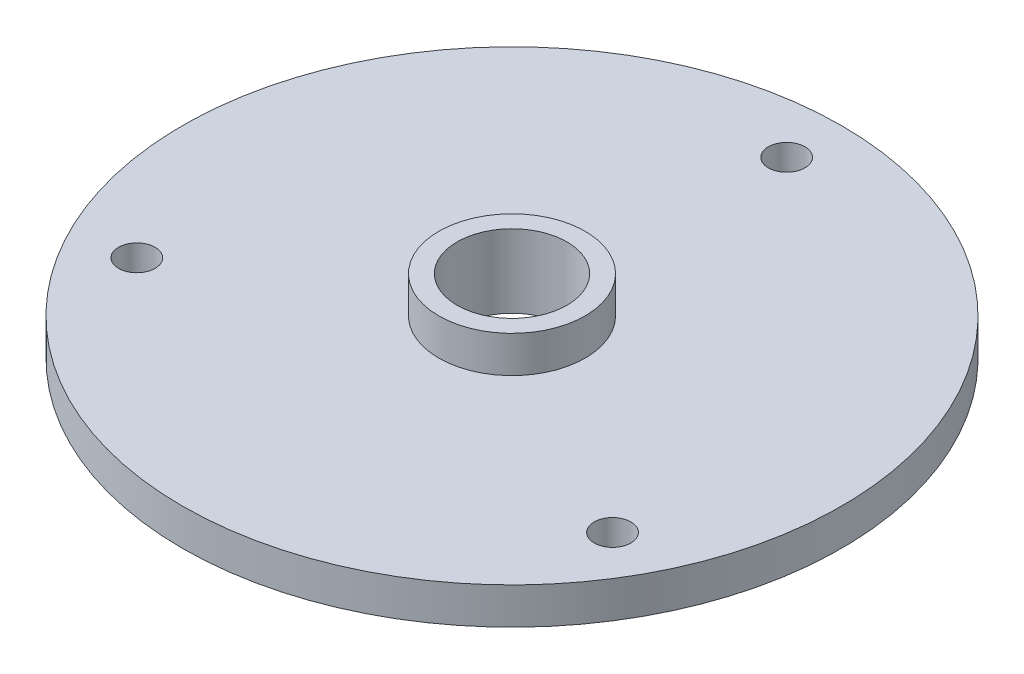
SolidWorks part; units mm, degrees
ref_plane "前视基准面" through (0, 0, 0) normal (0, 0, 1) x (1, 0, 0)
ref_plane "上视基准面" through (0, 0, 0) normal (0, 1, 0) x (1, 0, 0)
ref_plane "右视基准面" through (0, 0, 0) normal (1, 0, 0) x (0, 0, -1)
sketch "草图1" plane through (0, 0, 0) normal (0, 1, 0) x (1, 0, 0)
  line L0 (0, 0) -> (0, 22.2788) construction
  line L1 (0, 0) -> (39.8876, 0) construction
  circle A0 centre (0, 0) radius 18
  circle A1 centre (0, 0) radius 3
  circle A2 centre (0, 15) radius 1
  circle A3 centre (12.9904, -7.5) radius 1
  circle A4 centre (-12.9904, -7.5) radius 1
  point P14 (0, 0)
  dimension "D1" = 6
  dimension "D2" = 36
  dimension "D3" = 2
  dimension "D4" = 15
  dimension "D5" = 3
extrude "凸台-拉伸1" add sketch "草图1" along normal blind 2
sketch "草图2" plane through (0, 2, 0) normal (0, 1, 0) x (1, 0, 0)
  circle A0 centre (0, 0) radius 3
  circle A1 centre (0, 0) radius 4
  dimension "D1" = 8
extrude "凸台-拉伸2" add sketch "草图2" along normal blind 2
